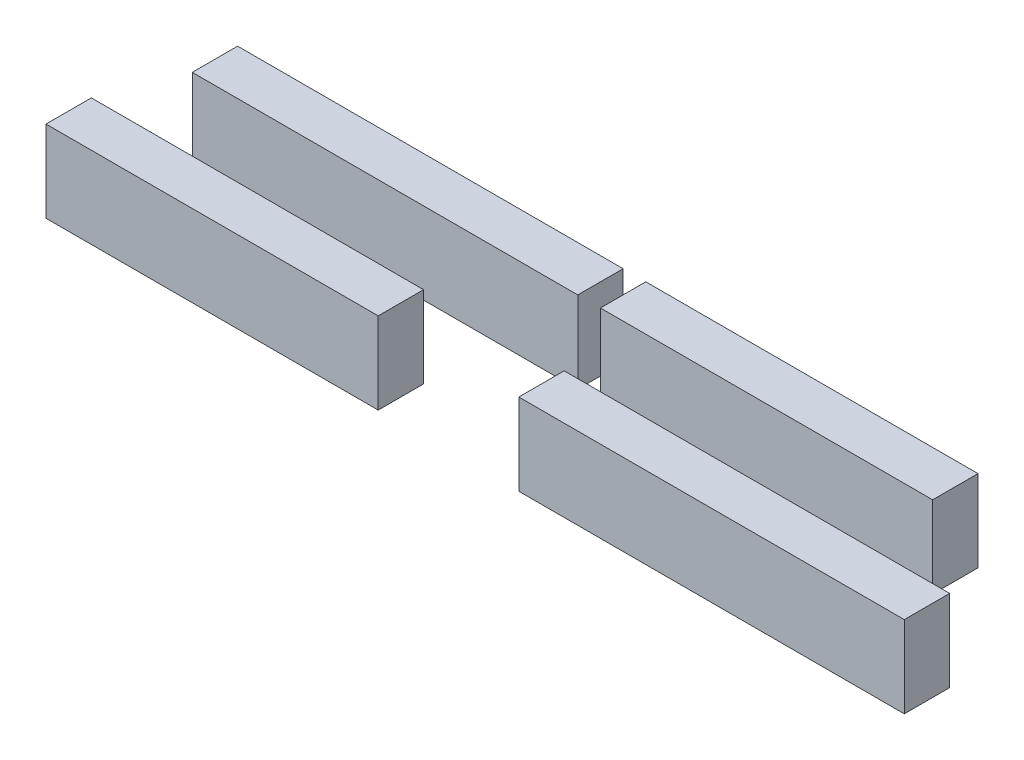
SolidWorks part; units mm, degrees
ref_plane "Front Plane" through (0, 0, 0) normal (0, 0, 1) x (1, 0, 0)
ref_plane "Top Plane" through (0, 0, 0) normal (0, 1, 0) x (1, 0, 0)
ref_plane "Right Plane" through (0, 0, 0) normal (1, 0, 0) x (0, 0, -1)
sketch "Sketch1" plane through (0, 0, 0) normal (0, 1, 0) x (1, 0, 0)
  line L0 (54.75, 9.5) -> (97.25, 9.5)
  line L1 (2.625, 9.5) -> (39.25, 9.5)
  line L2 (2.625, 9.5) -> (2.625, 4.5)
  line L3 (2.625, 4.5) -> (39.25, 4.5)
  line L4 (39.25, 9.5) -> (39.25, 4.5)
  line L5 (0, 0) -> (100, 0) construction
  line L6 (0, 0) -> (0, 75) construction
  line L7 (0, 75) -> (100, 75) construction
  line L8 (100, 0) -> (100, 75) construction
  line L9 (54.75, 9.5) -> (54.75, 4.5)
  line L10 (54.75, 4.5) -> (97.25, 4.5)
  line L11 (97.25, 9.5) -> (97.25, 4.5)
  line L12 (50.75, 22.5) -> (87.375, 22.5)
  line L13 (5.75, 22.5) -> (48.25, 22.5)
  line L14 (5.75, 22.5) -> (5.75, 17.5)
  line L15 (5.75, 17.5) -> (48.25, 17.5)
  line L16 (48.25, 22.5) -> (48.25, 17.5)
  line L17 (50.75, 22.5) -> (50.75, 17.5)
  line L18 (50.75, 17.5) -> (87.375, 17.5)
  line L19 (87.375, 22.5) -> (87.375, 17.5)
extrude "Boss-Extrude1" add sketch "Sketch1" along normal blind 9
